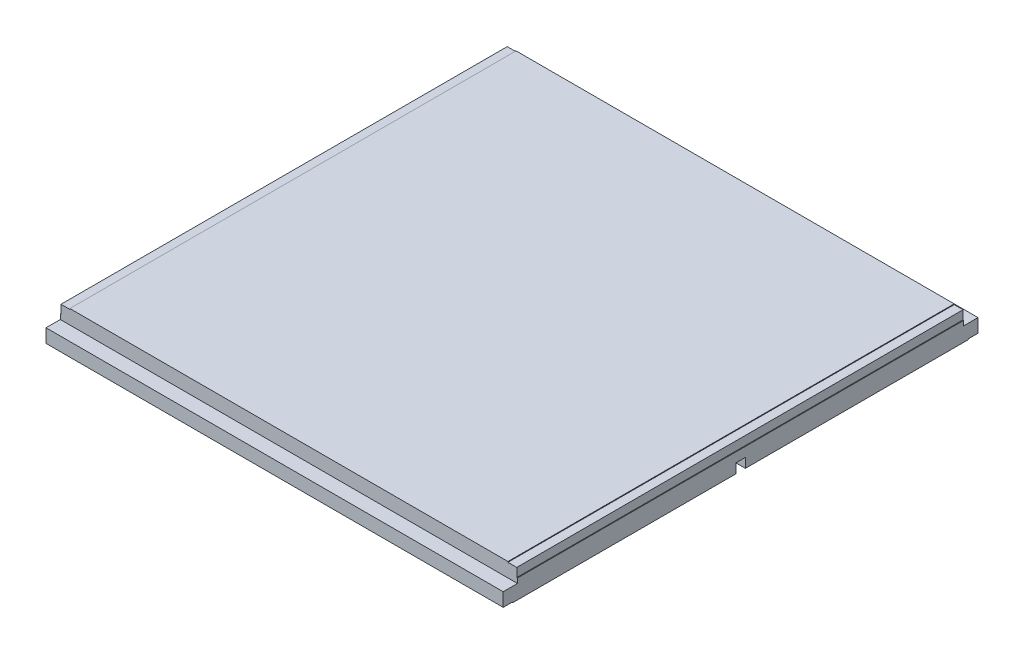
SolidWorks part; units mm, degrees
ref_plane "Front Plane" through (0, 0, 0) normal (0, 0, 1) x (1, 0, 0)
ref_plane "Top Plane" through (0, 0, 0) normal (0, 1, 0) x (1, 0, 0)
ref_plane "Right Plane" through (0, 0, 0) normal (1, 0, 0) x (0, 0, -1)
sketch "Sketch1" plane through (0, 0, 0) normal (0, 1, 0) x (1, 0, 0)
  line L1 (960, 997) -> (-960, 997)
  line L2 (960, 997) -> (960, -997)
  line L3 (960, -997) -> (-960, -997)
  line L4 (-960, 997) -> (-960, -997)
  line L5 (960, 997) -> (-960, -997) construction
  line L6 (960, -997) -> (-960, 997) construction
  point P0 (0, 0)
  dimension "D1" = 1994
  dimension "D2" = 1920
extrude "Boss-Extrude1" add sketch "Sketch1" along normal blind 120
ref_plane "Plane1" through (-960, 0, 0) normal (-1, 0, 0) x (0, 0, 1)
sketch "Sketch2" plane through (-960, 0, 0) normal (-1, 0, 0) x (0, 0, 1)
  line L0 (-997, 120) -> (997, 120) construction
  line L25 (-997, 120) -> (-937, 120)
  line L26 (-997, 120) -> (-997, 60)
  line L27 (937, 0) -> (937, 60)
  line L28 (-937, 60) -> (-937, 0)
  line L29 (937, 60) -> (-937, 60)
  line L30 (937, 0) -> (937, 60) construction
  line L31 (-937, 60) -> (-937, 0) construction
  line L32 (937, 60) -> (-937, 60) construction
  line L33 (-997, 60) -> (-937, 60)
  line L34 (-937, 120) -> (-937, 60)
  line L35 (997, 120) -> (937, 120)
  line L36 (997, 120) -> (997, 60)
  line L37 (997, 60) -> (937, 60)
  line L38 (937, 120) -> (937, 60)
  dimension "D2" = 60
  dimension "D1" = 60
extrude "Cut-Extrude1" cut sketch "Sketch2" against normal through all
ref_plane "Plane2" through (-960, 0, 0) normal (-1, 0, 0) x (0, 0, 1)
sketch "Sketch3" plane through (-960, 0, 0) normal (-1, 0, 0) x (0, 0, 1)
  line L0 (-20, 40) -> (20, 40)
  line L1 (0, 0) -> (0, 40) construction
  line L2 (20, 0) -> (20, 40)
  line L3 (-20, 0) -> (-20, 40)
  line L4 (-997, 40) -> (997, 40) construction
  line L5 (-997, 0) -> (997, 0) construction
  line L8 (937, 120) -> (-937, 120)
  line L9 (-937, 120) -> (-937, 60)
  line L10 (-937, 60) -> (-997, 60)
  line L11 (-997, 60) -> (-997, 0)
  line L12 (-997, 0) -> (997, 0)
  line L13 (997, 0) -> (997, 60)
  line L14 (997, 60) -> (937, 60)
  line L15 (937, 60) -> (937, 120)
  line L20 (-20, 0) -> (20, 0)
  line L21 (997, 0) -> (997, 60)
  dimension "D1" = 0
extrude "Cut-Extrude2" cut sketch "Sketch3" against normal through all contours L3 L20 L2 L0
ref_plane "Plane3" through (0, 0, 0) normal (0, -1, 0) x (-1, 0, 0)
sketch "Sketch4" plane through (0, 0, 0) normal (0, -1, 0) x (-1, 0, 0)
  line L0 (-960, 997) -> (960, 997) construction
  line L1 (-960, 997) -> (960, 997)
  line L2 (960, -997) -> (-960, -997) construction
  line L3 (960, -997) -> (-960, -997)
  line L4 (960, -957) -> (-960, -957)
  line L5 (-960, 957) -> (960, 957)
  line L6 (960, 957) -> (960, 997)
  line L7 (-960, 957) -> (-960, 997)
  line L8 (-960, -957) -> (-960, -997)
  line L9 (960, -957) -> (960, -997)
  dimension "D1" = 40
extrude "Cut-Extrude3" cut sketch "Sketch4" against normal blind 3
ref_plane "Plane4" through (0, 120, 0) normal (0, 1, 0) x (1, 0, 0)
sketch "Sketch5" plane through (0, 120, 0) normal (0, 1, 0) x (1, 0, 0)
  line L0 (960, -937) -> (960, 937) construction
  line L1 (-960, 937) -> (-960, -937) construction
  line L2 (-960, 937) -> (-920, 937)
  line L3 (-960, -937) -> (-920, -937)
  line L4 (920, -937) -> (960, -937)
  line L5 (920, 937) -> (960, 937)
  line L7 (960, -937) -> (960, 937)
  line L8 (-960, 937) -> (-960, -937)
  line L9 (920, -937) -> (920, 937)
  line L10 (-920, 937) -> (-920, -937)
  dimension "D1" = 40
extrude "Cut-Extrude4" cut sketch "Sketch5" against normal blind 3
ref_plane "Plane5" through (-960, 0, 0) normal (-1, 0, 0) x (0, 0, 1)
sketch "Sketch6" plane through (-960, 0, 0) normal (-1, 0, 0) x (0, 0, 1)
  line L0 (937, 120) -> (-937, 120) construction
  line L1 (937, 120) -> (-937, 120)
  line L2 (937, 80) -> (-937, 80)
  line L3 (-937, 120) -> (-937, 80)
  line L4 (937, 120) -> (937, 80)
  dimension "D1" = 40
extrude "Cut-Extrude5" cut sketch "Sketch6" against normal blind 3
mirror "Mirror1" about plane through (0, 0, 0) normal (1, 0, 0) of "Cut-Extrude5"
